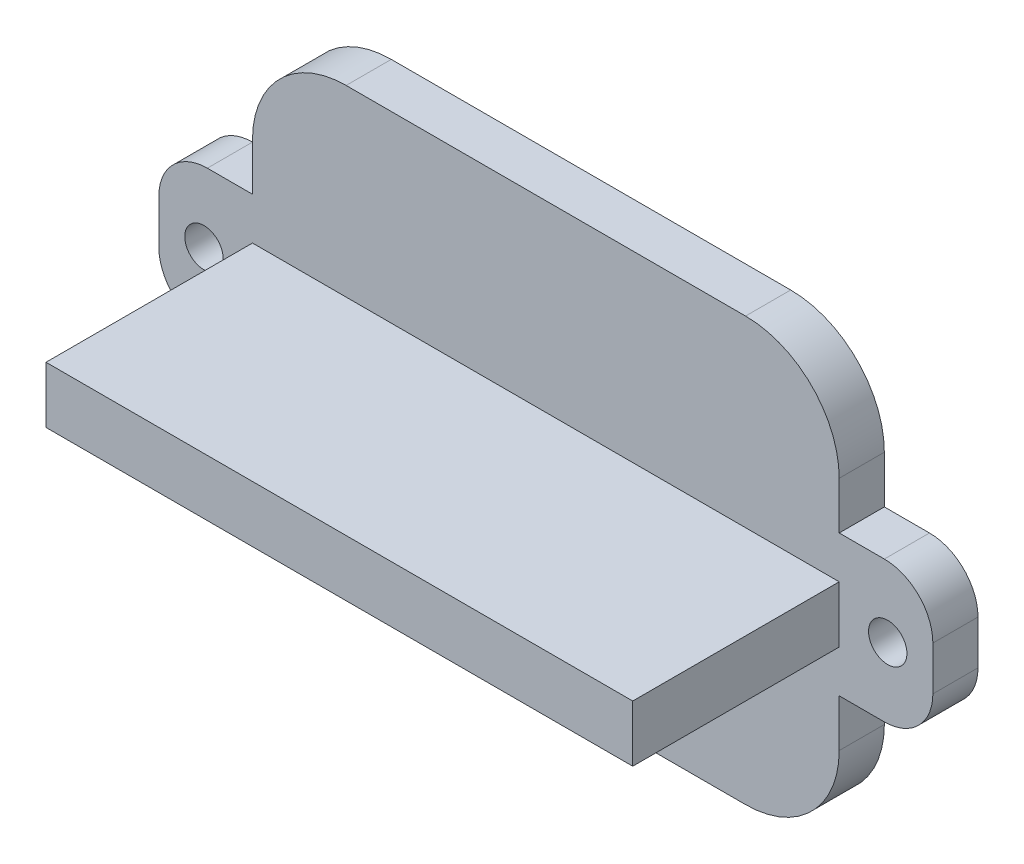
SolidWorks part; units mm, degrees
ref_plane "Alzado" through (0, 0, 0) normal (0, 0, 1) x (1, 0, 0)
ref_plane "Planta" through (0, 0, 0) normal (0, 1, 0) x (1, 0, 0)
ref_plane "Vista lateral" through (0, 0, 0) normal (1, 0, 0) x (0, 0, -1)
sketch "Croquis1" plane through (0, 0, 0) normal (0, 0, 1) x (1, 0, 0)
  line L0 (0, 0) -> (33.3839, 0) construction
  line L1 (8.85, -9.375) -> (-8.85, -9.375)
  line L2 (13, -5.225) -> (13, 5.225)
  line L3 (8.85, 9.375) -> (-8.85, 9.375)
  line L4 (-13, -5.225) -> (-13, 5.225)
  line L5 (13, -9.375) -> (-13, 9.375) construction
  line L6 (13, 9.375) -> (-13, -9.375) construction
  line L7 (0, 0) -> (-30.3, 0) construction
  line L8 (-13, 3.125) -> (24.0999, 3.125) construction
  line L9 (-13, -3.125) -> (24.0999, -3.125) construction
  line L11 (-13, -3.125) -> (-15, -3.125)
  line L12 (-13, -3.125) -> (-13, 3.125)
  line L13 (-13, 3.125) -> (-15, 3.125)
  line L14 (-17.15, -0.975) -> (-17.15, 0.975)
  line L15 (15, -3.125) -> (13, -3.125)
  line L16 (17.15, -0.975) -> (17.15, 0.975)
  line L17 (15, 3.125) -> (13, 3.125)
  line L18 (13, -3.125) -> (13, 3.125)
  circle A0 centre (-15.15, 0) radius 0.85
  circle A1 centre (15.15, 0) radius 0.85
  arc A2 (-15, 3.125) -> (-17.15, 0.975) centre (-15, 0.975) ccw
  arc A3 (-15, -3.125) -> (-17.15, -0.975) centre (-15, -0.975) cw
  arc A4 (17.15, 0.975) -> (15, 3.125) centre (15, 0.975) ccw
  arc A5 (15, -3.125) -> (17.15, -0.975) centre (15, -0.975) ccw
  arc A6 (-13, 5.225) -> (-8.85, 9.375) centre (-8.85, 5.225) cw
  arc A7 (-8.85, -9.375) -> (-13, -5.225) centre (-8.85, -5.225) cw
  arc A8 (13, 5.225) -> (8.85, 9.375) centre (8.85, 5.225) ccw
  arc A9 (8.85, -9.375) -> (13, -5.225) centre (8.85, -5.225) ccw
  point P0 (0, 0)
  point P8 (-15.15, 0)
  point P10 (15.15, 0)
  point P11 (-16, 0)
  point P12 (16, 0)
  point P13 (17.15, 0)
  point P14 (-17.15, 0)
  point P19 (-13, -3.125)
  point P20 (-13, 3.125)
  point P39 (17.15, -3.125)
  dimension "D11" = 2.15
  dimension "D12" = 2.15
  dimension "D13" = 2.15
  dimension "D14" = 2.15
  dimension "D15" = 4.15
  dimension "D16" = 4.15
  dimension "D17" = 4.15
  dimension "D18" = 4.15
  dimension "D1" = 18.75
  dimension "D2" = 26
  dimension "D3" = 2.15
  dimension "D4" = 2.15
  dimension "D5" = 3
  dimension "D6" = 4.15
  dimension "D7" = 4.15
  dimension "D8" = 3
  dimension "D9" = 6.25
  dimension "D10" = 6.25
extrude "Saliente-Extruir1" add sketch "Croquis1" along normal blind 2 contours L1 A9 L2 A8 L3 A6 L4 A7 | A3 L11 L4 L13 A2 L14 A0 | L15 A5 L16 A4 L17 L2 A1
sketch "Croquis2" plane through (0, 0, 0) normal (0, 0, 1) x (1, 0, 0)
  line L0 (-33.4877, 0) -> (31.6088, 0) construction
  line L1 (-13, -3.125) -> (-13, 3.125) construction
  line L3 (13, -3.125) -> (13, 3.125) construction
  line L4 (13, 1.2516) -> (-13, 1.2516)
  line L5 (13, 1.2516) -> (13, -1.2516)
  line L6 (13, -1.2516) -> (-13, -1.2516)
  line L7 (-13, 1.2516) -> (-13, -1.2516)
  line L8 (13, 1.2516) -> (-13, -1.2516) construction
  line L9 (13, -1.2516) -> (-13, 1.2516) construction
  point P5 (0, 0)
extrude "Saliente-Extruir3" add sketch "Croquis2" along normal blind 11.15
